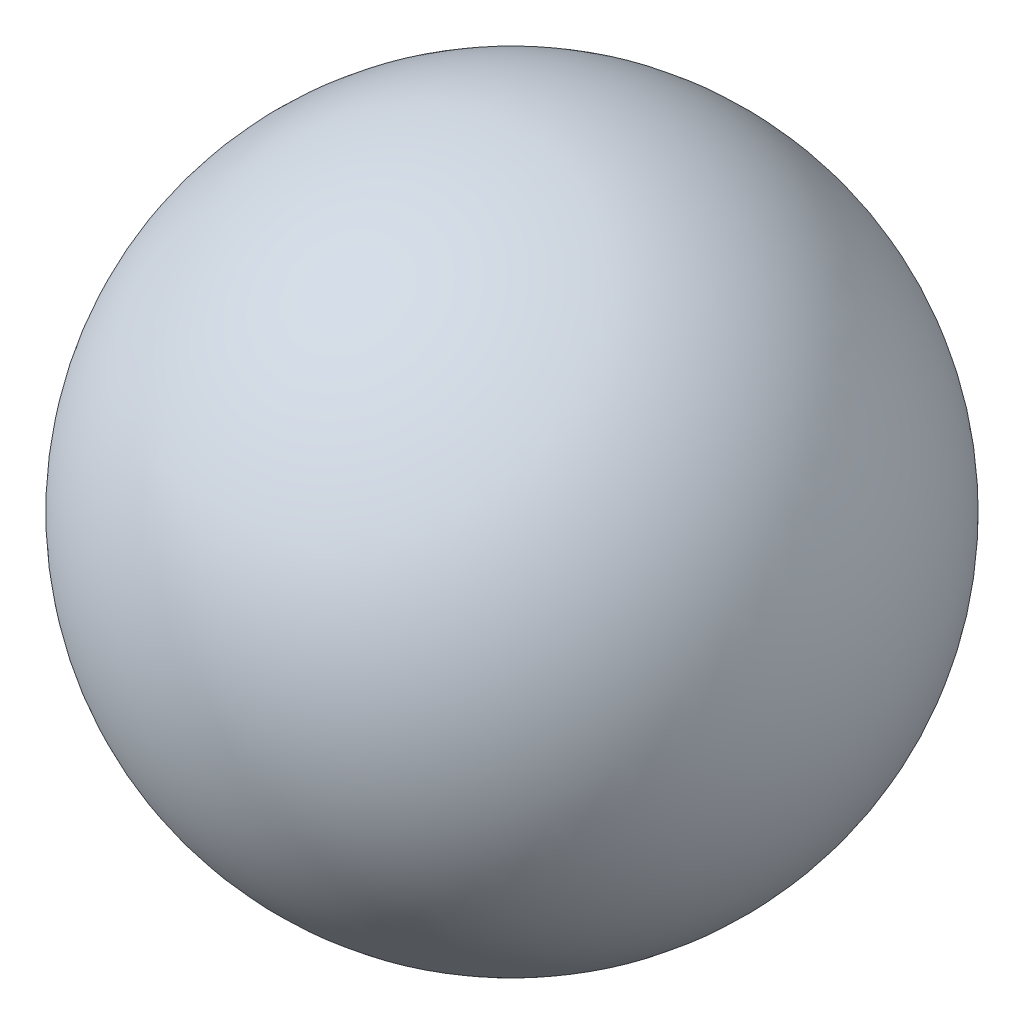
SolidWorks part; units mm, degrees
material "1.4511 (X3CrNb17)"
ref_plane "前视基准面" through (0, 0, 0) normal (0, 0, 1) x (1, 0, 0)
ref_plane "上视基准面" through (0, 0, 0) normal (0, 1, 0) x (1, 0, 0)
ref_plane "右视基准面" through (0, 0, 0) normal (1, 0, 0) x (0, 0, -1)
sketch "草图1" plane through (0, 0, 0) normal (0, 0, 1) x (1, 0, 0)
  line L0 (0, -3.111) -> (0, 3.7173) construction
  line L1 (0, 2.75) -> (0, -2.75)
  arc A0 (0, -2.75) -> (0, 2.75) centre (0, 0) ccw
  dimension "D1" = 5.5
revolve "旋转2" add sketch "草图1" angle 360 about L0
